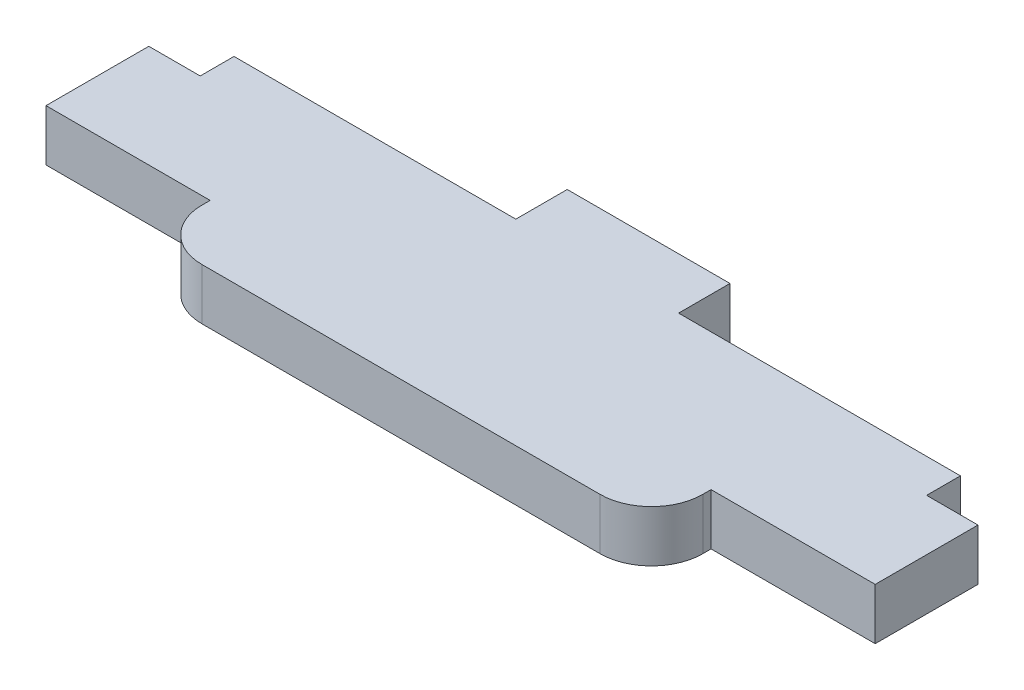
SolidWorks part; units mm, degrees
ref_plane "Front Plane" through (0, 0, 0) normal (0, 0, 1) x (1, 0, 0)
ref_plane "Top Plane" through (0, 0, 0) normal (0, 1, 0) x (1, 0, 0)
ref_plane "Right Plane" through (0, 0, 0) normal (1, 0, 0) x (0, 0, -1)
sketch "Sketch1" plane through (0, 0, 0) normal (0, 1, 0) x (1, 0, 0)
  line L0 (40.2069, 0.4057) -> (53.4968, 0.4057)
  line L3 (17.6158, 6.4057) -> (17.6158, 7.3645)
  line L4 (17.6158, 7.3645) -> (-1.5453, 7.3645)
  line L5 (-1.5453, 7.3645) -> (-1.5453, 19.3645)
  line L6 (37.3518, 29.3111) -> (56.3518, 29.3111)
  line L7 (95.2489, 7.3645) -> (95.2489, 19.3645)
  line L8 (95.2489, 7.3645) -> (76.0878, 7.3645)
  line L9 (76.0878, 7.3645) -> (76.0878, 6.4057)
  line L14 (70.0878, 0.4057) -> (53.4968, 0.4057)
  line L16 (-1.5453, 19.3645) -> (4.4547, 19.3645)
  line L17 (28.9745, 7.2378) -> (64.7291, 7.2378) construction
  line L18 (40.2069, 0.4057) -> (23.6158, 0.4057)
  line L19 (4.4547, 19.3645) -> (4.4547, 23.3111)
  line L23 (95.2489, 19.3645) -> (89.2489, 19.3645)
  line L24 (89.2489, 19.3645) -> (89.2489, 23.3111)
  line L25 (37.3518, 29.3111) -> (37.3518, 23.3111)
  line L26 (4.4547, 19.3645) -> (89.2489, 19.3645) construction
  line L27 (56.3518, 29.3111) -> (56.3518, 23.3111)
  line L28 (56.3518, 23.3111) -> (89.2489, 23.3111)
  line L30 (37.3518, 23.3111) -> (4.4547, 23.3111)
  arc A2 (76.0878, 6.4057) -> (70.0878, 0.4057) centre (70.0878, 6.4057) cw
  arc A3 (17.6158, 6.4057) -> (23.6158, 0.4057) centre (23.6158, 6.4057) ccw
  point P17 (46.8518, 29.3111)
  point P24 (46.8518, 7.2378)
  point P25 (46.8518, 20.4324)
  dimension "D1" = 6
extrude "Boss-Extrude1" add sketch "Sketch1" along normal blind 6
